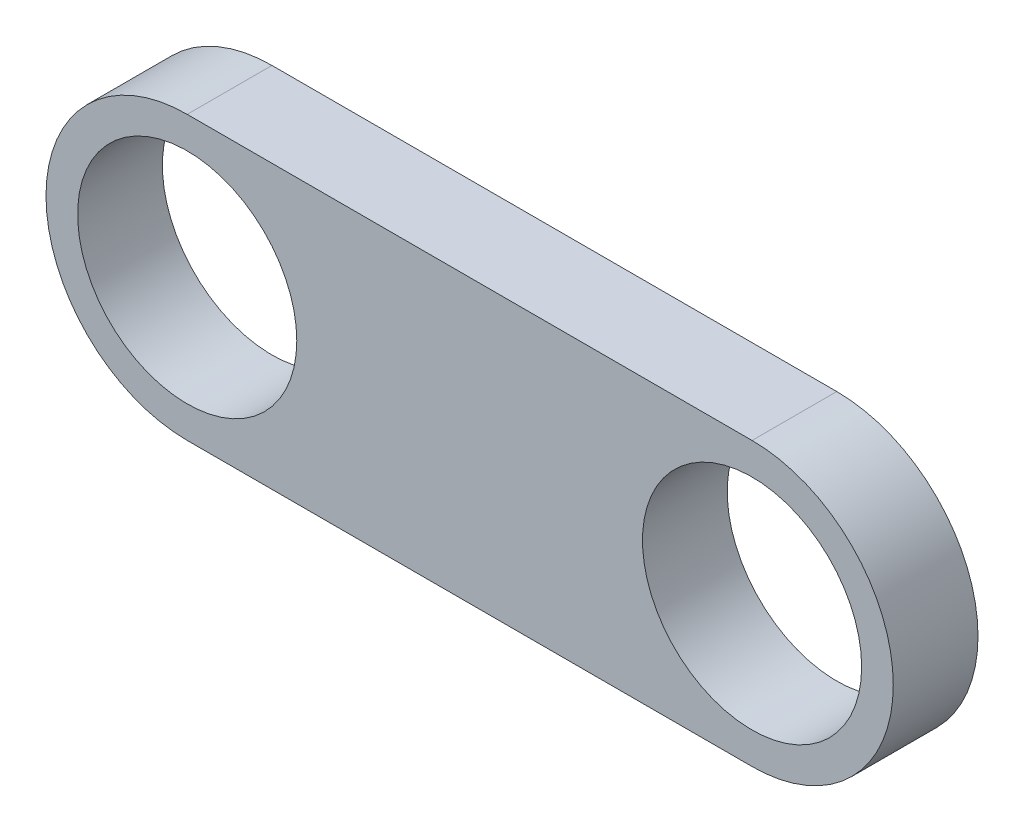
SolidWorks part; units mm, degrees
ref_plane "Front Plane" through (0, 0, 0) normal (0, 0, 1) x (1, 0, 0)
ref_plane "Top Plane" through (0, 0, 0) normal (0, 1, 0) x (1, 0, 0)
ref_plane "Right Plane" through (0, 0, 0) normal (1, 0, 0) x (0, 0, -1)
sketch "Sketch1" plane through (0, 0, 0) normal (0, 0, 1) x (1, 0, 0)
  line L1 (-12.202, -4.8946) -> (7.798, -4.8946)
  line L3 (-12.202, 5.1054) -> (7.798, 5.1054)
  arc A0 (-12.202, 5.1054) -> (-12.202, -4.8946) centre (-12.202, 0.1054) ccw
  arc A1 (7.798, 5.1054) -> (7.798, -4.8946) centre (7.798, 0.1054) cw
  circle A2 centre (-12.202, 0.1054) radius 3.88
  circle A3 centre (7.798, 0.1054) radius 3.88
  dimension "D3" = 7.76
  dimension "D4" = 7.76
  dimension "D1" = 10
  dimension "D2" = 20
extrude "Boss-Extrude1" add sketch "Sketch1" along normal blind 3
